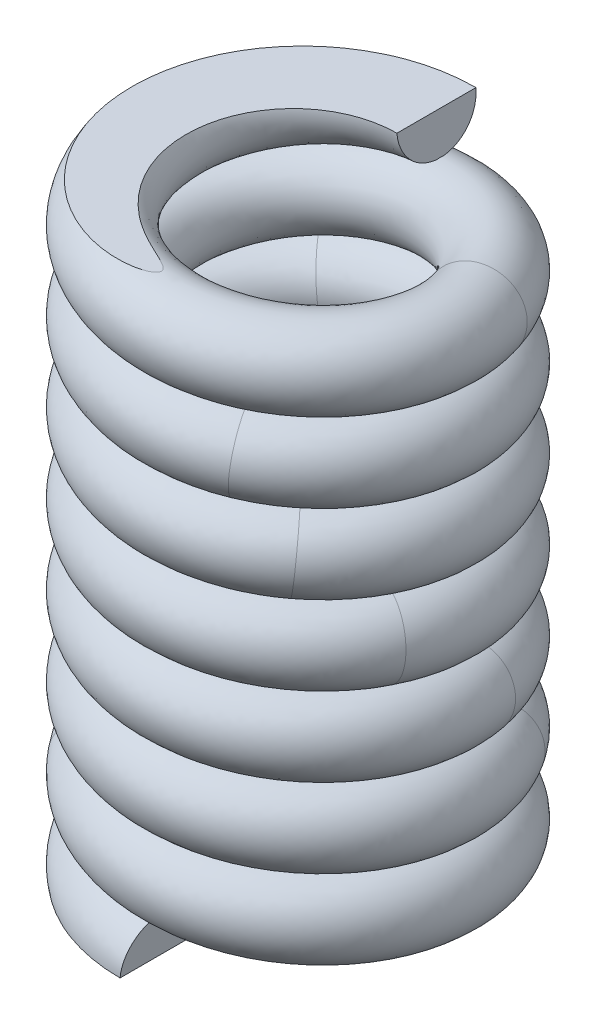
SolidWorks part; units mm, degrees
ref_plane "Front Plane" through (0, 0, 0) normal (0, 0, 1) x (1, 0, 0)
ref_plane "Top Plane" through (0, 0, 0) normal (0, 1, 0) x (1, 0, 0)
ref_plane "Right Plane" through (0, 0, 0) normal (1, 0, 0) x (0, 0, -1)
sketch "Sketch1" plane through (0, 0, 0) normal (0, 1, 0) x (1, 0, 0)
  circle A0 centre (0, 0) radius 3.5
curve "Helix/Spiral1" pitch 2 height 15 turns 7.5
sweep "Sweep1" add path "Helix/Spiral1" circular profile diameter 2 parameters "D3"=2
sketch "Sketch8" plane through (0, 0, 0) normal (0, 1, 0) x (1, 0, 0)
  circle A0 centre (0, 0) radius 5
extrude "Cut-Extrude1" cut sketch "Sketch8" against normal blind 10
ref_plane "Plane1" through (0, 15, 0) normal (0, -1, 0) x (-1, 0, 0)
sketch "Sketch9" plane through (0, 15, 0) normal (0, -1, 0) x (-1, 0, 0)
  circle A1 centre (0, 0) radius 5
  circle A2 centre (0, 0) radius 5
  dimension "D1" = 0
extrude "Cut-Extrude2" cut sketch "Sketch9" against normal blind 10
